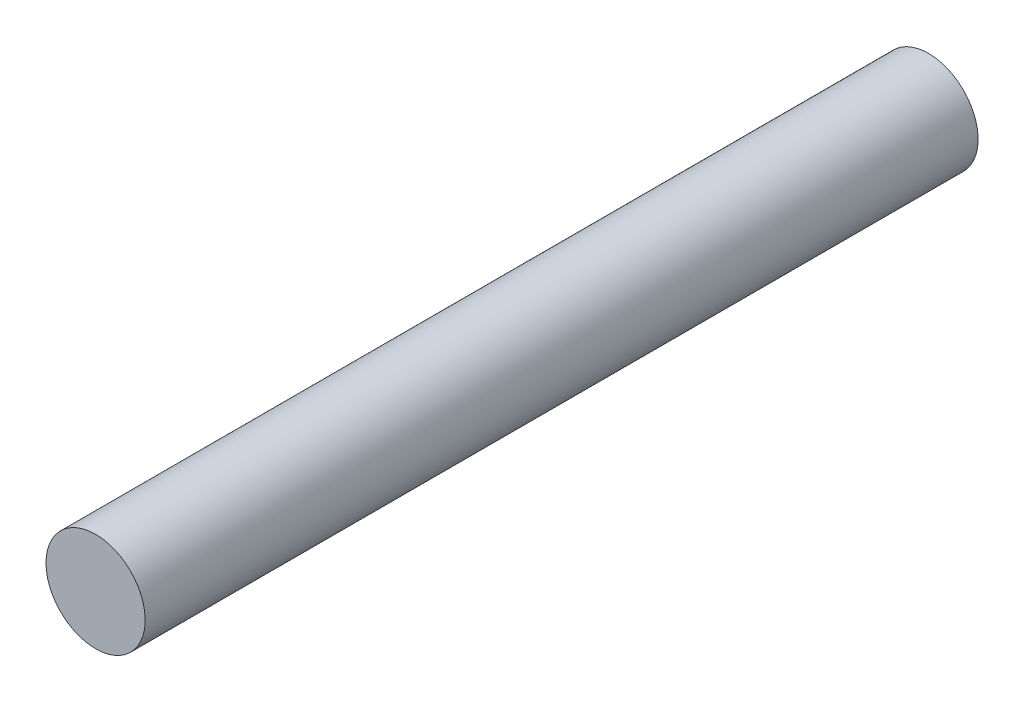
SolidWorks part; units mm, degrees
ref_plane "Front Plane" through (0, 0, 0) normal (0, 0, 1) x (1, 0, 0)
ref_plane "Top Plane" through (0, 0, 0) normal (0, 1, 0) x (1, 0, 0)
ref_plane "Right Plane" through (0, 0, 0) normal (1, 0, 0) x (0, 0, -1)
sketch "Sketch1" plane through (0, 0, 0) normal (0, 0, 1) x (1, 0, 0)
  circle A0 centre (0, 0) radius 5
  dimension "D1" = 10
extrude "Boss-Extrude1" add sketch "Sketch1" along normal blind 84
